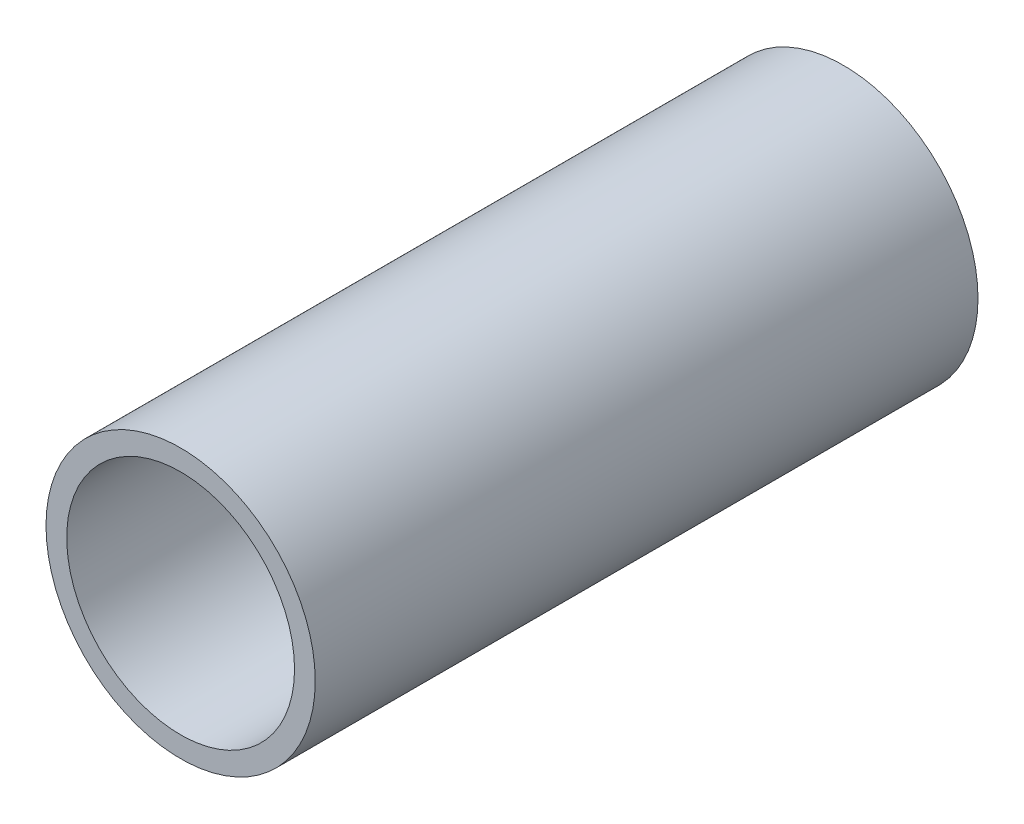
SolidWorks part; units mm, degrees
ref_plane "Front Plane" through (0, 0, 0) normal (0, 0, 1) x (1, 0, 0)
ref_plane "Top Plane" through (0, 0, 0) normal (0, 1, 0) x (1, 0, 0)
ref_plane "Right Plane" through (0, 0, 0) normal (1, 0, 0) x (0, 0, -1)
sketch "Sketch2" plane through (0, 0, 0) normal (0, 0, 1) x (1, 0, 0)
  circle A0 centre (0, 0) radius 32.5
  dimension "D1" = 65
extrude "Boss-Extrude1" add sketch "Sketch2" along normal mid plane 160
sketch "Sketch3" plane through (0, 0, 80) normal (0, 0, 1) x (1, 0, 0)
  circle A0 centre (0, 0) radius 27.5
  dimension "D1" = 55
extrude "Cut-Extrude1" cut sketch "Sketch3" against normal through all contours A0
